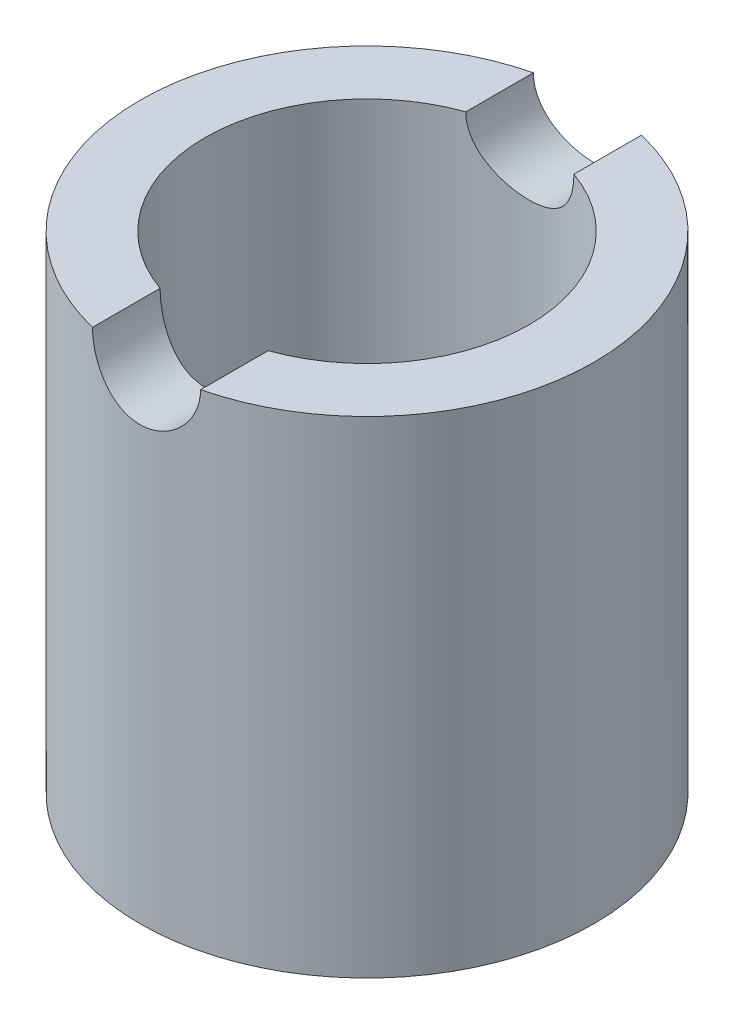
SolidWorks part; units mm, degrees
ref_plane "正面" through (0, 0, 0) normal (0, 0, 1) x (1, 0, 0)
ref_plane "平面" through (0, 0, 0) normal (0, 1, 0) x (1, 0, 0)
ref_plane "右側面" through (0, 0, 0) normal (1, 0, 0) x (0, 0, -1)
sketch "ｽｹｯﾁ1" plane through (0, 0, 0) normal (0, 1, 0) x (1, 0, 0)
  circle A0 centre (0, 0) radius 3
  circle A1 centre (0, 0) radius 4.2
  dimension "D1" = 6
  dimension "D2" = 1.2
extrude "ﾎﾞｽ - 押し出し1" add sketch "ｽｹｯﾁ1" along normal blind 13.5
sketch "ｽｹｯﾁ2" plane through (0, 0, 0) normal (0, 0, 1) x (1, 0, 0)
  line L0 (0, 0) -> (0, 13.5) construction
  line L1 (4.2, 13.5) -> (-4.2, 13.5) construction
  circle A0 centre (0, 12.5) radius 1
  dimension "D1" = 2
sketch "ｽｹｯﾁ3" plane through (0, 13.5, 0) normal (0, 1, 0) x (1, 0, 0)
  circle A1 centre (0, 0) radius 4.2
  circle A2 centre (0, 0) radius 4.2
  dimension "D1" = 0
extrude "ｶｯﾄ - 押し出し3" cut sketch "ｽｹｯﾁ3" against normal blind 1
sketch "ｽｹｯﾁ4" plane through (0, 0, 0) normal (0, 0, 1) x (1, 0, 0)
  circle A0 centre (0, 12.5) radius 1 construction
  circle A1 centre (0, 12.5) radius 1
extrude "ｶｯﾄ - 押し出し4" cut sketch "ｽｹｯﾁ4" against normal mid plane 100
other "面の移動1" face at (0, 0, 4.2) parameters "D1"=3.5
